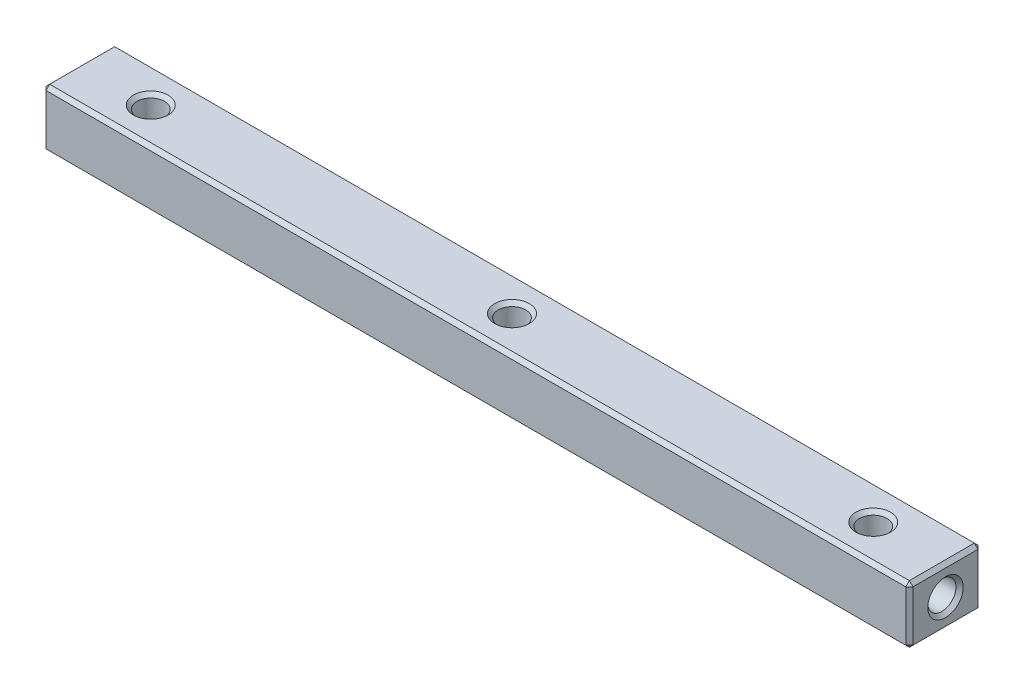
SolidWorks part; units mm, degrees
ref_plane "Front Plane" through (0, 0, 0) normal (0, 0, 1) x (1, 0, 0)
ref_plane "Top Plane" through (0, 0, 0) normal (0, 1, 0) x (1, 0, 0)
ref_plane "Right Plane" through (0, 0, 0) normal (1, 0, 0) x (0, 0, -1)
sketch "Sketch1" plane through (0, 0, 0) normal (0, 1, 0) x (1, 0, 0)
  line L0 (-60, 0) -> (60, 0) construction
  line L1 (-60, 5) -> (60, 5)
  line L2 (-60, 5) -> (-60, -5)
  line L3 (-60, -5) -> (60, -5)
  line L4 (60, 5) -> (60, -5)
  line L5 (-60, 5) -> (60, -5) construction
  line L6 (-60, -5) -> (60, 5) construction
  line L7 (0, 5) -> (0, -5) construction
  line L8 (-50, -1.9) -> (-25, -1.9) construction
  line L9 (-25, -1.9) -> (0, -1.9) construction
  circle A0 centre (-50, 0) radius 1.9
  circle A1 centre (50, 0) radius 1.9
  circle A4 centre (0, 0) radius 1.9
  point P0 (0, 0)
  dimension "D3" = 3.8
  dimension "D1" = 120
  dimension "D2" = 10
  dimension "D4" = 10
extrude "Boss-Extrude1" add sketch "Sketch1" along normal mid plane 8
sketch "Sketch2" plane through (-60, 0, 0) normal (-1, 0, 0) x (0, 0, 1)
  line L0 (-5, 4) -> (5, -4) construction
  circle A0 centre (0, 0) radius 1.95
  dimension "D1" = 3.9
extrude "Cut-Extrude1" cut sketch "Sketch2" against normal blind 8
mirror "Mirror1" about plane through (0, 0, 0) normal (1, 0, 0) of "Cut-Extrude1"
chamfer "Chamfer1" distance 0.5 angle 45 20 edges at (-60, 0, 1.95) (60, 0, 1.95) (50, -4, -1.9) (-50, -4, 1.9) (50, 4, -1.9) (60, 0, -5) (-60, 0, -5) (0, -4, -5) (-60, -4, 0) (60, -4, 0) (-60, 0, 5) (0, -4, 5) (60, 0, 5) (0, 4, 5) (-60, 4, 0) (0, 4, -5) (60, 4, 0) (-50, 4, 1.9) (0, -4, 1.9) (0, 4, 1.9)
